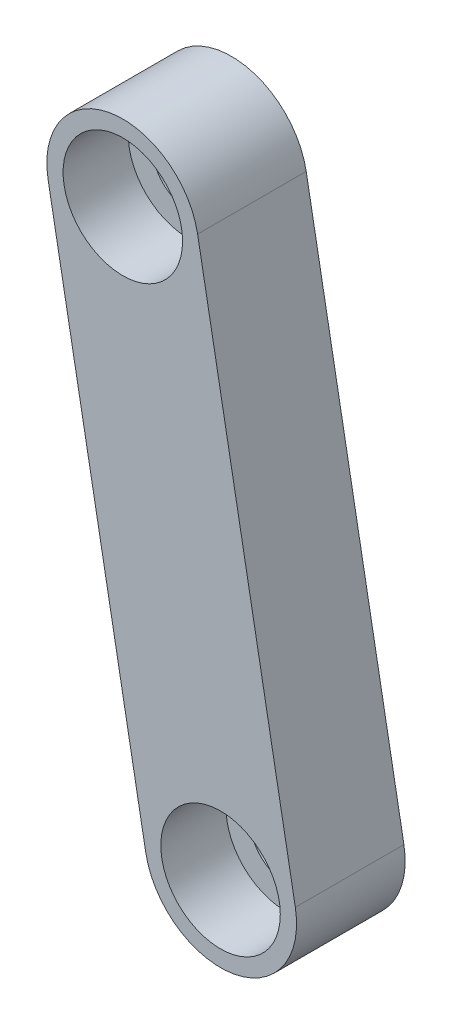
SolidWorks part; units mm, degrees
ref_plane "Front Plane" through (0, 0, 0) normal (0, 0, 1) x (1, 0, 0)
ref_plane "Top Plane" through (0, 0, 0) normal (0, 1, 0) x (1, 0, 0)
ref_plane "Right Plane" through (0, 0, 0) normal (1, 0, 0) x (0, 0, -1)
sketch "Sketch1" plane through (0, 0, 0) normal (0, 0, 1) x (1, 0, 0)
  line L0 (-14.5518, 56.1792) -> (-10.0535, 31.5873)
  line L1 (-3.1671, 32.847) -> (-7.6661, 57.4388)
  arc A0 (-10.0535, 31.5873) -> (-3.1671, 32.847) centre (-6.6103, 32.2172) ccw
  arc A1 (-7.6661, 57.4388) -> (-14.5518, 56.1792) centre (-11.1089, 56.809) ccw
  circle A2 centre (-6.61, 32.2171) radius 1.625
  circle A4 centre (-11.1089, 56.809) radius 1.625
extrude "Boss-Extrude1" add sketch "Sketch1" along normal blind 5
sketch "Sketch2" plane through (0, 0, 5) normal (0, 0, 1) x (1, 0, 0)
  circle A0 centre (-11.1089, 56.809) radius 2.75
  circle A1 centre (-6.61, 32.2171) radius 2.75
extrude "Cut-Extrude1" cut sketch "Sketch2" against normal blind 3
